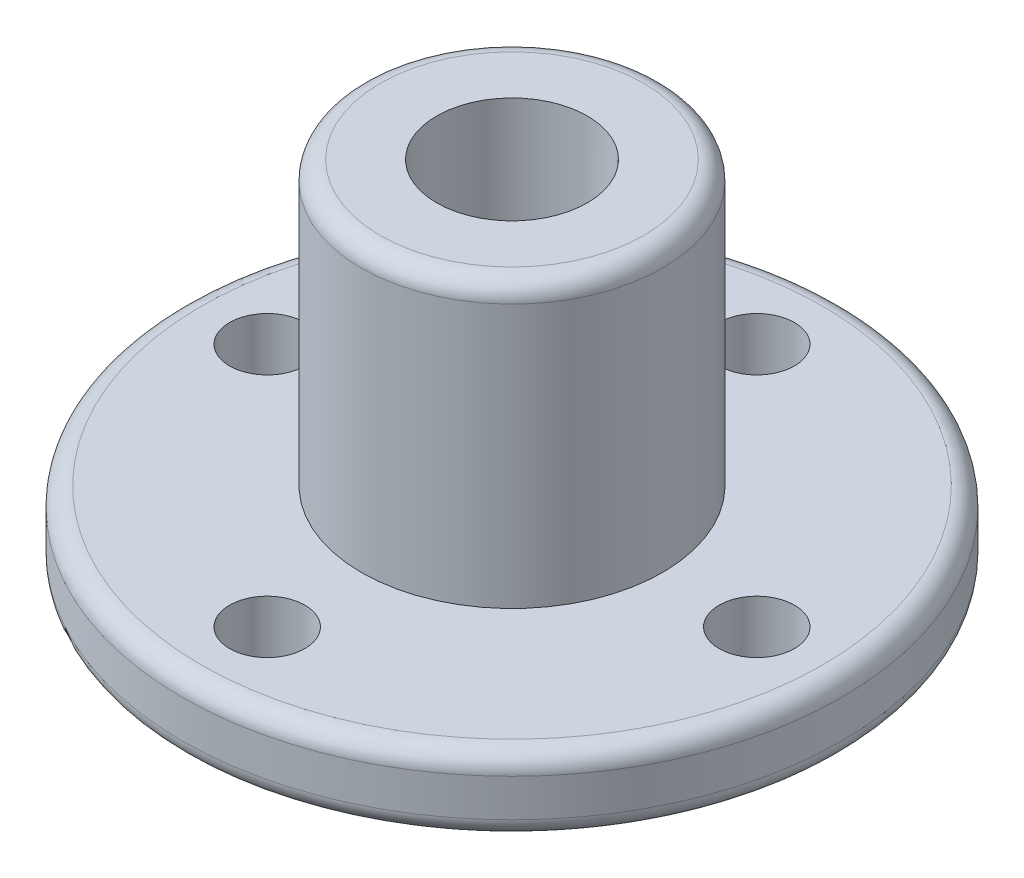
SolidWorks part; units mm, degrees
ref_plane "前视基准面" through (0, 0, 0) normal (0, 0, 1) x (1, 0, 0)
ref_plane "上视基准面" through (0, 0, 0) normal (0, 1, 0) x (1, 0, 0)
ref_plane "右视基准面" through (0, 0, 0) normal (1, 0, 0) x (0, 0, -1)
sketch "草图1" plane through (0, 0, 0) normal (0, 1, 0) x (1, 0, 0)
  circle A0 centre (0, 0) radius 17.5
  dimension "D1" = 35
extrude "凸台-拉伸1" add sketch "草图1" along normal blind 4
sketch "草图2" plane through (0, 4, 0) normal (0, 1, 0) x (1, 0, 0)
  circle A0 centre (0, 0) radius 8
  circle A1 centre (0, 0) radius 4
  dimension "D1" = 8
  dimension "D2" = 16
extrude "凸台-拉伸2" add sketch "草图2" along normal blind 15
sketch "草图3" plane through (0, 0, 0) normal (0, 0, 1) x (1, 0, 0)
  circle A0 centre (0, 12) radius 2
  dimension "D1" = 4
  dimension "D2" = 12
extrude "切除-拉伸1" cut sketch "草图3" against normal up to next
fillet "圆角1" radius 1 3 edges at (0, 19, 8) (0, 4, 17.5) (0, 0, 17.5)
sketch "草图4" plane through (0, 4, 0) normal (0, 1, 0) x (1, 0, 0)
  circle A0 centre (-13, 0) radius 2
  circle A1 centre (0, -13) radius 2
  circle A2 centre (0, 13) radius 2
  circle A3 centre (13, 0) radius 2
  point P12 (0, 0)
  dimension "D1" = 4
  dimension "D2" = 13
  dimension "D3" = 4
extrude "切除-拉伸2" cut sketch "草图4" against normal blind 15
